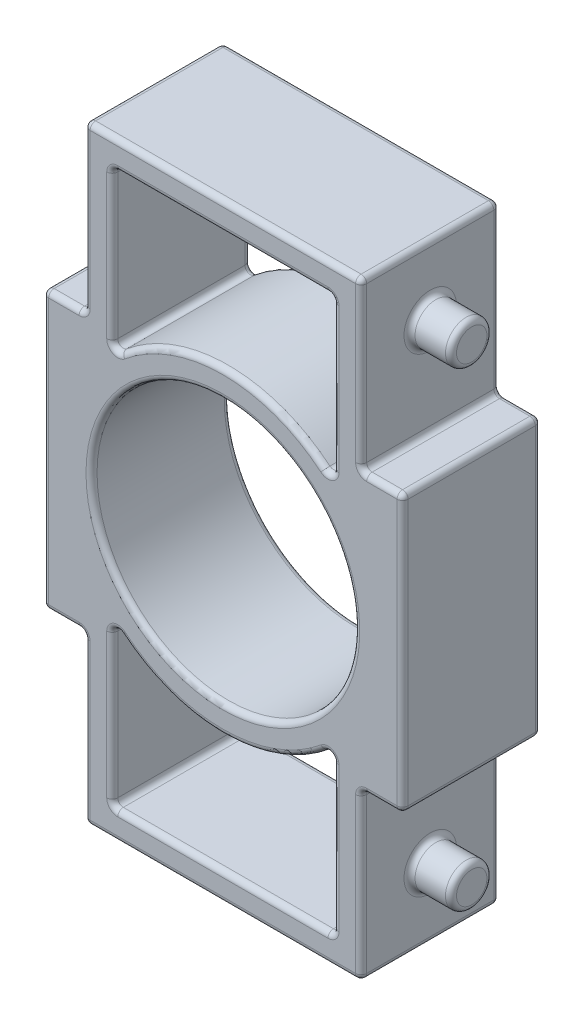
SolidWorks part; units mm, degrees
material "7075-O (SS)"
ref_plane "Front Plane" through (0, 0, 0) normal (0, 0, 1) x (1, 0, 0)
ref_plane "Top Plane" through (0, 0, 0) normal (0, 1, 0) x (1, 0, 0)
ref_plane "Right Plane" through (0, 0, 0) normal (1, 0, 0) x (0, 0, -1)
sketch "Sketch1" plane through (0, 0, 0) normal (1, 0, 0) x (0, 0, -1)
  line L1 (25, -110) -> (-25, -110)
  line L2 (25, -110) -> (25, 110)
  line L3 (25, 110) -> (-25, 110)
  line L4 (-25, -110) -> (-25, 110)
  line L5 (25, -110) -> (-25, 110) construction
  line L6 (25, 110) -> (-25, -110) construction
  point P0 (0, 0)
  dimension "D1" = 50
  dimension "D2" = 220
extrude "Boss-Extrude1" add sketch "Sketch1" along normal mid plane 100
sketch "Sketch2" plane through (50, 0, 0) normal (1, 0, 0) x (0, 0, -1)
  line L0 (0, 85) -> (0, -85) construction
  line L1 (0, 0) -> (50000, 0) construction
  circle A0 centre (0, 85) radius 7.5
  circle A1 centre (0, -85) radius 7.5
  dimension "D2" = 15
  dimension "D1" = 170
extrude "Boss-Extrude2" add sketch "Sketch2" along normal blind 15
mirror "Mirror1" about plane through (0, 0, 0) normal (1, 0, 0) of "Boss-Extrude2"
sketch "Sketch5" plane through (0, 0, 25) normal (0, 0, 1) x (1, 0, 0)
  line L0 (-50, 110) -> (-50, -110) construction
  line L1 (-50, 50) -> (-65, 50)
  line L2 (-50, 50) -> (-50, -50)
  line L3 (-50, -50) -> (-65, -50)
  line L4 (-65, 50) -> (-65, -50)
  line L5 (-65, 0) -> (0, 0) construction
  dimension "D1" = 100
  dimension "D2" = 65
extrude "Boss-Extrude3" add sketch "Sketch5" against normal up to surface (50 mm away) up to face at (0, 0, -25)
mirror "Mirror2" about plane through (0, 0, 0) normal (1, 0, 0) of "Boss-Extrude3"
sketch "Sketch3" plane through (0, 0, -25) normal (0, 0, -1) x (-1, 0, 0)
  circle A0 centre (0, 0) radius 47.5
  dimension "D1" = 95
extrude "Cut-Extrude1" cut sketch "Sketch3" against normal through all
sketch "Sketch4" plane through (0, 0, -25) normal (0, 0, -1) x (-1, 0, 0)
  line L8 (40, -100) -> (40, -40)
  line L9 (40, 100) -> (-40, 100)
  line L10 (-40, 100) -> (-40, 40)
  line L11 (-40, -100) -> (40, -100)
  line L12 (40, -100) -> (40, -41.3068)
  line L13 (40, 100) -> (-40, 100)
  line L14 (-40, 100) -> (-40, 41.3068)
  line L15 (-40, -100) -> (40, -100)
  line L22 (40, -40) -> (55, -40)
  line L24 (55, -40) -> (55, 40)
  line L26 (55, 40) -> (40, 40)
  line L28 (40, 40) -> (40, 100)
  line L29 (40, 41.3068) -> (40, 100)
  line L30 (-40, 40) -> (-55, 40)
  line L32 (-55, 40) -> (-55, -40)
  line L34 (-55, -40) -> (-40, -40)
  line L36 (-40, -40) -> (-40, -100)
  line L37 (-40, -41.3068) -> (-40, -100)
  arc A0 (-40, -41.3068) -> (40, -41.3068) centre (0, 0) ccw
  circle A2 centre (0, 0) radius 47.5 construction
  arc A4 (40, 41.3068) -> (-40, 41.3068) centre (0, 0) ccw
  point P13 (0, 0)
  dimension "D2" = 10
  dimension "D1" = 10
extrude "Cut-Extrude2" cut sketch "Sketch4" against normal through all
fillet "Fillet1" radius 2 70 edges at (40, 70.6534, -25) (0, 100, -25) (0, -100, -25) (-40, -70.6534, -25) (0, -100, 25) (-40, -70.6534, 25) (-40, -100, 0) (0, 100, 25) (40, 70.6534, 25) (-47.5, 0, -25) (-47.5, 0, 25) (-50, -85, -7.5) (-65, -85, -7.5) (-50, 85, -7.5) (-65, 85, -7.5) (50, -85, -7.5) (65, -85, -7.5) (50, 85, -7.5) (65, 85, -7.5) (-50, 80, 25) (-50, -80, 25) (-50, 110, 0) (50, -80, 25) (50, 80, 25) (50, -110, 0) (50, 80, -25) (50, -80, -25) (50, 110, 0) (0, 110, 25) (0, 110, -25) (0, -110, 25) (0, -110, -25) (-50, -80, -25) (-50, 80, -25) (-50, -110, 0) (-57.5, 50, -25) (-57.5, 50, 25) (-57.5, -50, -25) (-57.5, -50, 25) (-65, 0, -25) (-65, 0, 25) (-50, -50, 0) (-65, -50, 0) (-65, 50, 0) (-50, 50, 0) (57.5, 50, -25) (57.5, 50, 25) (65, 0, -25) (65, 0, 25) (57.5, -50, -25) (57.5, -50, 25) (50, 50, 0) (65, 50, 0) (65, -50, 0) (50, -50, 0) (-40, -41.3068, 0) (0, -57.5, 25) (0, -57.5, -25) (40, 41.3068, 0) (40, 100, 0) (0, 57.5, 25) (0, 57.5, -25) (40, -100, 0) (40, -41.3068, 0) (40, -70.6534, 25) (40, -70.6534, -25) (-40, 100, 0) (-40, 41.3068, 0) (-40, 70.6534, 25) (-40, 70.6534, -25)
